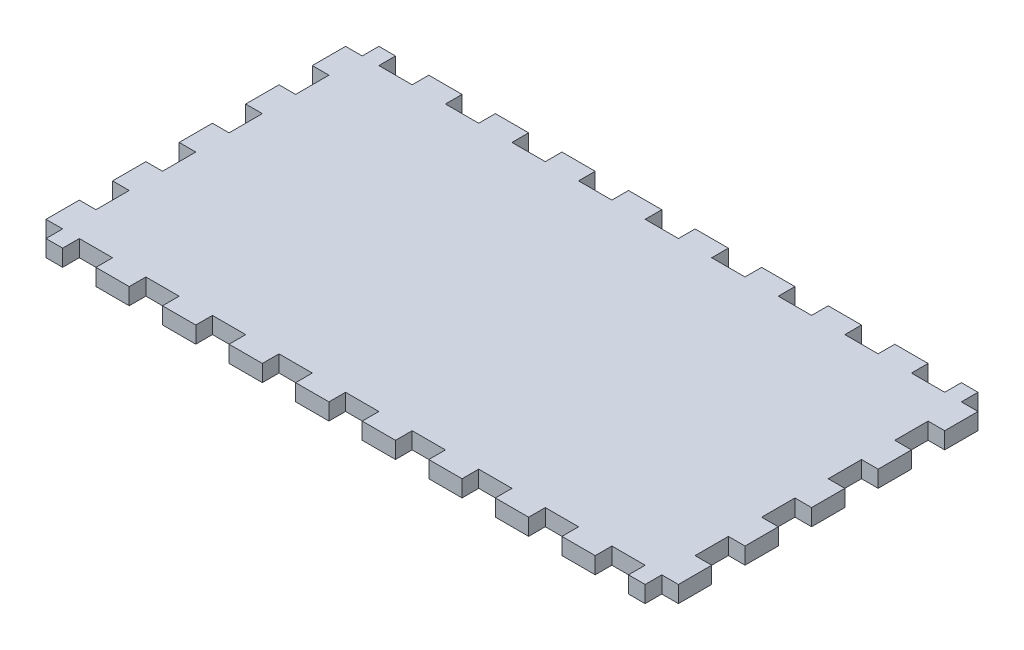
SolidWorks part; units mm, degrees
ref_plane "Front Plane" through (0, 0, 0) normal (0, 0, 1) x (1, 0, 0)
ref_plane "Top Plane" through (0, 0, 0) normal (0, 1, 0) x (1, 0, 0)
ref_plane "Right Plane" through (0, 0, 0) normal (1, 0, 0) x (0, 0, -1)
sketch "Sketch2" plane through (0, 0, 0) normal (0, 1, 0) x (1, 0, 0)
  line L40 (-1.5184, 22.7243) -> (-191.5184, 22.7243) construction
  line L59 (-96.5184, 22.7243) -> (-96.5184, 11.9258) construction
  line L60 (-4.0184, -10) -> (-4.0184, -20)
  line L63 (-4.0184, -30) -> (-4.0184, -40)
  line L64 (-4.0184, -50) -> (-4.0184, -60)
  line L65 (-4.0184, -70) -> (-4.0184, -80)
  line L67 (0.9816, -80) -> (0.9816, -90)
  line L68 (-4.0184, -80) -> (0.9816, -80)
  line L69 (0.9816, -70) -> (-4.0184, -70)
  line L70 (0.9816, -60) -> (0.9816, -70)
  line L71 (-4.0184, -60) -> (0.9816, -60)
  line L72 (0.9816, -50) -> (-4.0184, -50)
  line L73 (0.9816, -40) -> (0.9816, -50)
  line L74 (-4.0184, -40) -> (0.9816, -40)
  line L75 (0.9816, -30) -> (-4.0184, -30)
  line L76 (0.9816, -20) -> (0.9816, -30)
  line L77 (-4.0184, -20) -> (0.9816, -20)
  line L78 (0.9816, -10) -> (-4.0184, -10)
  line L79 (0.9816, 0) -> (0.9816, -10)
  line L84 (-179.0184, -95) -> (-179.0184, -90)
  line L85 (-179.0184, -90) -> (-169.0184, -90)
  line L86 (-169.0184, -90) -> (-169.0184, -95)
  line L87 (-169.0184, -95) -> (-159.0184, -95)
  line L88 (-159.0184, -95) -> (-159.0184, -90)
  line L89 (-159.0184, -90) -> (-149.0184, -90)
  line L90 (-149.0184, -90) -> (-149.0184, -95)
  line L91 (-149.0184, -95) -> (-139.0184, -95)
  line L92 (-139.0184, -95) -> (-139.0184, -90)
  line L93 (-139.0184, -90) -> (-129.0184, -90)
  line L94 (-129.0184, -90) -> (-129.0184, -95)
  line L95 (-129.0184, -95) -> (-119.0184, -95)
  line L96 (-119.0184, -95) -> (-119.0184, -90)
  line L97 (-119.0184, -90) -> (-109.0184, -90)
  line L98 (-109.0184, -90) -> (-109.0184, -95)
  line L99 (-109.0184, -95) -> (-99.0184, -95)
  line L100 (-99.0184, -95) -> (-99.0184, -90)
  line L101 (-99.0184, -90) -> (-89.0184, -90)
  line L102 (-89.0184, -90) -> (-89.0184, -95)
  line L103 (-89.0184, -95) -> (-79.0184, -95)
  line L104 (-79.0184, -95) -> (-79.0184, -90)
  line L105 (-79.0184, -90) -> (-69.0184, -90)
  line L106 (-69.0184, -90) -> (-69.0184, -95)
  line L107 (-69.0184, -95) -> (-59.0184, -95)
  line L108 (-59.0184, -95) -> (-59.0184, -90)
  line L109 (-59.0184, -90) -> (-49.0184, -90)
  line L110 (-49.0184, -90) -> (-49.0184, -95)
  line L111 (-49.0184, -95) -> (-39.0184, -95)
  line L112 (-39.0184, -95) -> (-39.0184, -90)
  line L113 (-39.0184, -90) -> (-29.0184, -90)
  line L114 (-29.0184, -90) -> (-29.0184, -95)
  line L115 (-29.0184, -95) -> (-19.0184, -95)
  line L116 (-19.0184, -95) -> (-19.0184, -90)
  line L117 (-19.0184, -90) -> (-9.0184, -90)
  line L118 (-9.0184, -90) -> (-9.0184, -95)
  line L124 (-189.0184, 0) -> (-184.0184, 0)
  line L125 (-4.0184, -95) -> (-4.0184, -90)
  line L127 (-195.1999, -90) -> (-195.1999, -45) construction
  line L128 (-9.0184, -95) -> (-4.0184, -95)
  line L129 (-195.1999, -45) -> (-204.7982, -45) construction
  line L130 (-179.0184, -95) -> (-184.0184, -95)
  line L132 (0.9816, -90) -> (-4.0184, -90)
  line L133 (-4.0184, -106.4545) -> (-184.0184, -106.4545) construction
  line L134 (-94.0184, -106.4545) -> (-94.0184, -114.8566) construction
  line L135 (0.9816, 0) -> (-4.0184, 0)
  line L136 (-189.0184, 0) -> (-189.0184, -10)
  line L137 (-189.0184, -10) -> (-184.0184, -10)
  line L138 (-184.0184, -10) -> (-184.0184, -20)
  line L139 (-184.0184, -20) -> (-189.0184, -20)
  line L140 (-189.0184, -20) -> (-189.0184, -30)
  line L141 (-189.0184, -30) -> (-184.0184, -30)
  line L142 (-184.0184, -30) -> (-184.0184, -40)
  line L143 (-184.0184, -40) -> (-189.0184, -40)
  line L144 (-189.0184, -40) -> (-189.0184, -50)
  line L145 (-189.0184, -50) -> (-184.0184, -50)
  line L146 (-184.0184, -50) -> (-184.0184, -60)
  line L147 (-184.0184, -60) -> (-189.0184, -60)
  line L148 (-189.0184, -60) -> (-189.0184, -70)
  line L149 (-189.0184, -70) -> (-184.0184, -70)
  line L150 (-184.0184, -70) -> (-184.0184, -80)
  line L151 (-184.0184, -80) -> (-189.0184, -80)
  line L152 (-189.0184, -80) -> (-189.0184, -90)
  line L153 (-189.0184, -90) -> (-184.0184, -90)
  line L154 (-184.0184, -95) -> (-184.0184, -90)
  line L155 (-184.0184, 5) -> (-184.0184, 0)
  line L156 (-179.0184, 5) -> (-184.0184, 5)
  line L157 (-9.0184, 5) -> (-4.0184, 5)
  line L158 (-4.0184, 5) -> (-4.0184, 0)
  line L159 (-9.0184, 0) -> (-9.0184, 5)
  line L160 (-19.0184, 0) -> (-9.0184, 0)
  line L161 (-19.0184, 5) -> (-19.0184, 0)
  line L162 (-29.0184, 5) -> (-19.0184, 5)
  line L163 (-29.0184, 0) -> (-29.0184, 5)
  line L164 (-39.0184, 0) -> (-29.0184, 0)
  line L165 (-39.0184, 5) -> (-39.0184, 0)
  line L166 (-49.0184, 5) -> (-39.0184, 5)
  line L167 (-49.0184, 0) -> (-49.0184, 5)
  line L168 (-59.0184, 0) -> (-49.0184, 0)
  line L169 (-59.0184, 5) -> (-59.0184, 0)
  line L170 (-69.0184, 5) -> (-59.0184, 5)
  line L171 (-69.0184, 0) -> (-69.0184, 5)
  line L172 (-79.0184, 0) -> (-69.0184, 0)
  line L173 (-79.0184, 5) -> (-79.0184, 0)
  line L174 (-89.0184, 5) -> (-79.0184, 5)
  line L175 (-89.0184, 0) -> (-89.0184, 5)
  line L176 (-99.0184, 0) -> (-89.0184, 0)
  line L177 (-99.0184, 5) -> (-99.0184, 0)
  line L178 (-109.0184, 5) -> (-99.0184, 5)
  line L179 (-109.0184, 0) -> (-109.0184, 5)
  line L180 (-119.0184, 0) -> (-109.0184, 0)
  line L181 (-119.0184, 5) -> (-119.0184, 0)
  line L182 (-129.0184, 5) -> (-119.0184, 5)
  line L183 (-129.0184, 0) -> (-129.0184, 5)
  line L184 (-139.0184, 0) -> (-129.0184, 0)
  line L185 (-139.0184, 5) -> (-139.0184, 0)
  line L186 (-149.0184, 5) -> (-139.0184, 5)
  line L187 (-149.0184, 0) -> (-149.0184, 5)
  line L188 (-159.0184, 0) -> (-149.0184, 0)
  line L189 (-159.0184, 5) -> (-159.0184, 0)
  line L190 (-169.0184, 5) -> (-159.0184, 5)
  line L191 (-169.0184, 0) -> (-169.0184, 5)
  line L192 (-179.0184, 0) -> (-169.0184, 0)
  line L193 (-179.0184, 5) -> (-179.0184, 0)
  dimension "D5" = 10
  dimension "D8" = 5
  dimension "D12" = 10
  dimension "D17" = 5
  dimension "D13" = 9
extrude "Boss-Extrude3" add sketch "Sketch2" along normal blind 5
